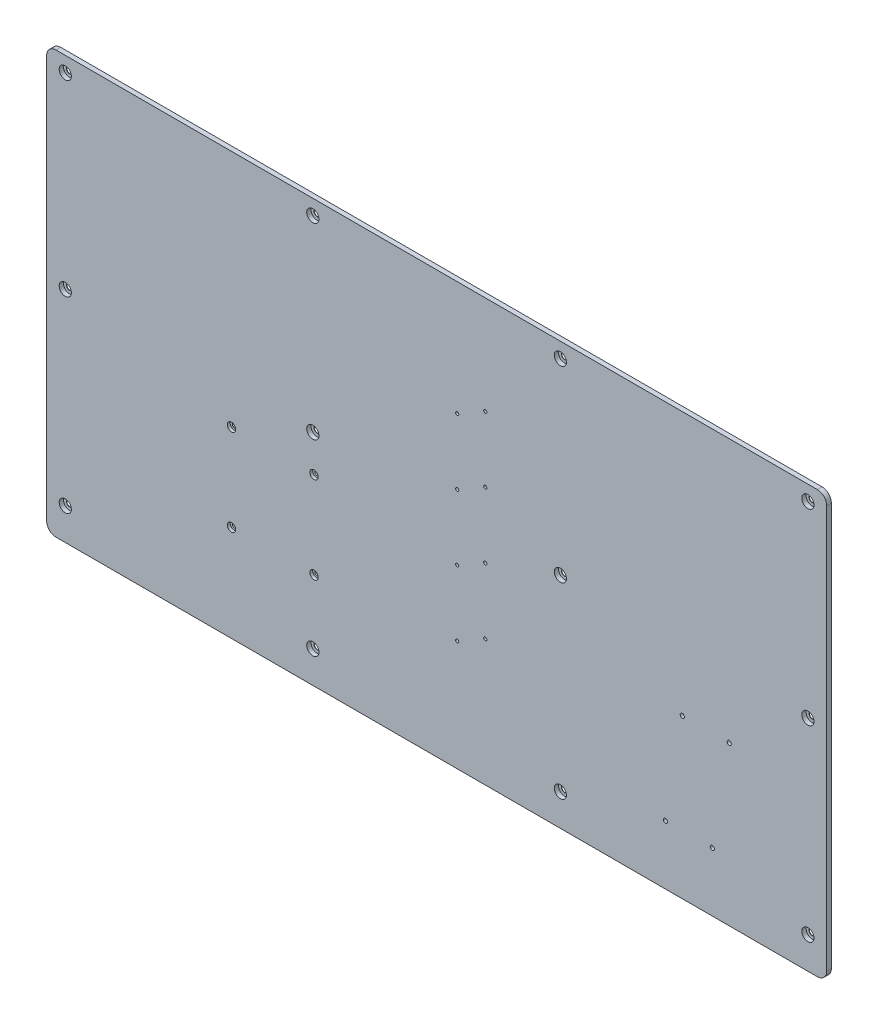
SolidWorks part; units mm, degrees
ref_plane "Plan de face" through (0, 0, 0) normal (0, 0, 1) x (1, 0, 0)
ref_plane "Plan de dessus" through (0, 0, 0) normal (0, 1, 0) x (1, 0, 0)
ref_plane "Plan de droite" through (0, 0, 0) normal (1, 0, 0) x (0, 0, -1)
sketch "Esquisse1" plane through (0, 0, 0) normal (0, 0, 1) x (1, 0, 0)
  line L1 (-406, -225) -> (406, -225)
  line L2 (-416, -215) -> (-416, 215)
  line L3 (-406, 225) -> (406, 225)
  line L4 (416, -215) -> (416, 215)
  line L5 (-416, -225) -> (416, 225) construction
  line L6 (-416, 225) -> (416, -225) construction
  arc A0 (416, 215) -> (406, 225) centre (406, 215) ccw
  arc A1 (406, -225) -> (416, -215) centre (406, -215) ccw
  arc A2 (-406, -225) -> (-416, -215) centre (-406, -215) cw
  arc A3 (-416, 215) -> (-406, 225) centre (-406, 215) cw
  point P0 (0, 0)
  dimension "D3" = 10
  dimension "D1" = 832
  dimension "D2" = 450
extrude "Boss.-Extru.1" add sketch "Esquisse1" along normal blind 5
hole_wizard "Dégagement M61" positions "Esquisse3" profile "Esquisse2" hole size "M6" standard "JIS" end condition through all
sketch "Esquisse3" plane through (0, 0, 0) normal (0, 0, -1) x (-1, 0, 0)
  point P0 (-395.9198, 208.8724)
sketch "Esquisse2" plane through (395.9198, 208.8724, 0) normal (1, 0, 0) x (0, 1, 0)
  line L0 (0, 0) -> (0, 5)
  line L1 (0, 5) -> (3.3, 5)
  line L2 (3.3, 5) -> (3.3, 0)
  line L5 (3.3, 0) -> (0, 0)
  line L11 (0, -6.35) -> (0, 107.95) construction
  dimension "Diamètre du perçage jusqu'au prochain" = 6.6
  dimension "Profondeur du perçage jusqu'au prochain" = 5
hole_wizard "Chambrage pour vis à tête ronde bombée M61" positions "Esquisse5" profile "Esquisse4" counterbore size "M6" standard "Ansi Metric" end condition through all
sketch "Esquisse5" plane through (0, 0, 5) normal (0, 0, 1) x (1, 0, 0)
  point P0 (395.9198, 208.8724)
sketch "Esquisse4" plane through (395.9198, 208.8724, 5) normal (1, 0, 0) x (0, -1, 0)
  line L0 (0, 0) -> (0, 5)
  line L1 (0, 5) -> (3.3, 5)
  line L2 (3.3, 4.625) -> (3.3, 5)
  line L3 (3.3, 4.625) -> (3.325, 4.6)
  line L4 (3.325, 4.6) -> (6.5, 4.6)
  line L5 (6.5, 4.6) -> (6.5, 0)
  line L7 (0, 0) -> (6.5, 0)
  line L9 (-3.3, 4.625) -> (-3.325, 4.6) construction
  line L11 (0, -6.35) -> (0, 107.95) construction
  dimension "Diamètre du perçage jusqu'au prochain" = 6.6
  dimension "Profondeur du perçage jusqu'au prochain" = 5
  dimension "Diamètre du chambrage" = 13
  dimension "Profondeur du chambrage" = 4.6
  dimension "Diamètre du fraisage milieu" = 6.65
  dimension "Angle du fraisage milieu" = 90
pattern_linear "Répétition linéaire1" count 5 spacing 100 along (0, -1, 0) count 4 spacing 264 along (-1, 0, 0) skipping (1, 0), (1, 1), (1, 2), (1, 3), (3, 0), (3, 1), (3, 2), (3, 3) of "Chambrage pour vis à tête ronde bombée M61"
hole_wizard "Chambrage pour vis à tête ronde bombée M42" positions "Esquisse10" profile "Esquisse9" counterbore size "M4" standard "Ansi Metric" end condition through all
sketch "Esquisse10" plane through (0, 0, 5) normal (0, 0, 1) x (1, 0, 0)
  point P0 (-130.8155, -122.2563)
  point P2 (-130.8155, -29.7118)
sketch "Esquisse9" plane through (-130.8155, -122.2563, 5) normal (1, 0, 0) x (0, -1, 0)
  line L0 (0, 0) -> (0, 5)
  line L1 (0, 5) -> (2.25, 5)
  line L2 (2.25, 3.125) -> (2.25, 5)
  line L3 (2.25, 3.125) -> (2.275, 3.1)
  line L4 (2.275, 3.1) -> (4.5, 3.1)
  line L5 (4.5, 3.1) -> (4.5, 0)
  line L7 (0, 0) -> (4.5, 0)
  line L9 (-2.25, 3.125) -> (-2.275, 3.1) construction
  line L11 (0, -6.35) -> (0, 107.95) construction
  dimension "Diamètre du perçage jusqu'au prochain" = 4.5
  dimension "Profondeur du perçage jusqu'au prochain" = 5
  dimension "Diamètre du chambrage" = 9
  dimension "Profondeur du chambrage" = 3.1
  dimension "Diamètre du fraisage milieu" = 4.55
  dimension "Angle du fraisage milieu" = 90
pattern_linear "Répétition linéaire3" count 2 spacing 88 along (-1, 0, 0) of "Chambrage pour vis à tête ronde bombée M42"
hole_wizard "M3 Clearance Hole1" positions "Sketch2" profile "Sketch1" hole size "M3" standard "ANSI Metric" end condition through all
sketch "Sketch2" plane through (0, 0, 5) normal (0, 0, 1) x (1, 0, 0)
  point P0 (21.8921, -106.9135)
  point P3 (51.8921, -89.9135)
sketch "Sketch1" plane through (21.8921, -106.9135, 5) normal (1, 0, 0) x (0, -1, 0)
  line L0 (0, 0) -> (0, 5)
  line L1 (0, 5) -> (1.7, 5)
  line L2 (1.7, 5) -> (1.7, 0)
  line L5 (1.7, 0) -> (0, 0)
  line L11 (0, -6.35) -> (0, 107.95) construction
  dimension "Thru Hole Dia." = 3.4
  dimension "Thru Hole Depth" = 5
pattern_linear "LPattern1" count 4 spacing 70 along (0, 1, 0) of "M3 Clearance Hole1"
hole_wizard "M4 Clearance Hole1" positions "Sketch4" profile "Sketch3" hole size "M4" standard "ANSI Metric" end condition through all
sketch "Sketch4" plane through (0, 0, 5) normal (0, 0, 1) x (1, 0, 0)
  point P0 (294, -162)
  point P3 (244, -162)
  point P6 (312, -56)
  point P9 (262, -56)
sketch "Sketch3" plane through (294, -162, 5) normal (1, 0, 0) x (0, -1, 0)
  line L0 (0, 0) -> (0, 5)
  line L1 (0, 5) -> (2.25, 5)
  line L2 (2.25, 5) -> (2.25, 0)
  line L5 (2.25, 0) -> (0, 0)
  line L11 (0, -6.35) -> (0, 107.95) construction
  dimension "Thru Hole Dia." = 4.5
  dimension "Thru Hole Depth" = 5
